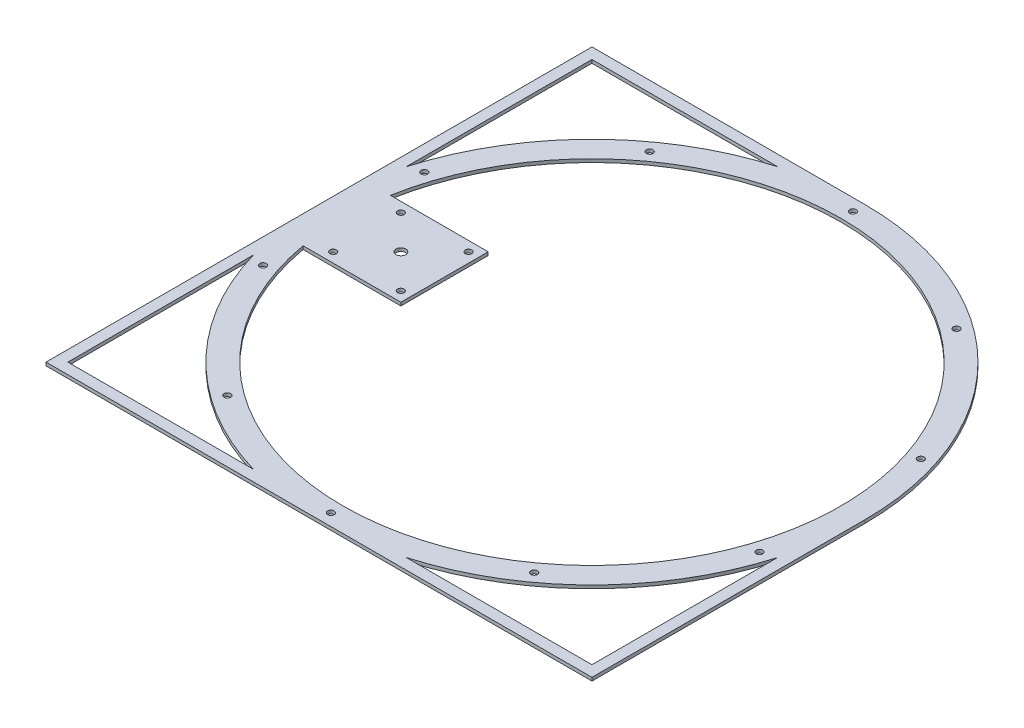
SolidWorks part; units mm, degrees
ref_plane "Front Plane" through (0, 0, 0) normal (0, 0, 1) x (1, 0, 0)
ref_plane "Top Plane" through (0, 0, 0) normal (0, 1, 0) x (1, 0, 0)
ref_plane "Right Plane" through (0, 0, 0) normal (1, 0, 0) x (0, 0, -1)
sketch "Sketch1" plane through (0, 0, 0) normal (0, 1, 0) x (1, 0, 0)
  line L0 (-125, 0) -> (-125, -5.475) construction
  line L1 (0, 0) -> (-250, 0)
  line L2 (0, 0) -> (0, -250)
  line L3 (0, -250) -> (-250, -250)
  line L4 (-250, 0) -> (-250, -250)
  circle A0 centre (-125, -125) radius 125
  circle A1 centre (-125, -5.475) radius 1.5
  circle A2 centre (-11.325, -88.0647) radius 1.5
  circle A3 centre (-54.745, -221.6978) radius 1.5
  circle A4 centre (-195.255, -221.6978) radius 1.5
  circle A5 centre (-238.675, -88.0647) radius 1.5
  circle A6 centre (-54.745, -28.3022) radius 1.5
  circle A7 centre (-11.325, -88.0647) radius 1.5
  circle A8 centre (-11.325, -161.9353) radius 1.5
  circle A9 centre (-54.745, -221.6978) radius 1.5
  circle A10 centre (-125, -244.525) radius 1.5
  circle A11 centre (-195.255, -221.6978) radius 1.5
  circle A12 centre (-238.675, -161.9353) radius 1.5
  circle A13 centre (-238.675, -88.0647) radius 1.5
  circle A14 centre (-195.255, -28.3022) radius 1.5
  point P21 (-125, -125)
  point P40 (-125, -125)
  dimension "D2" = 3
  dimension "D1" = 250
  dimension "D3" = 5
  dimension "D4" = 10
extrude "Boss-Extrude1" add sketch "Sketch1" along normal blind 1.5
sketch "Sketch2" plane through (0, 1.5, 0) normal (0, 1, 0) x (1, 0, 0)
  line L0 (-250, 0) -> (0, -250) construction
  line L1 (-228, -109.5) -> (-197, -109.5) construction
  line L2 (-228, -109.5) -> (-228, -140.5) construction
  line L3 (-228, -140.5) -> (-197, -140.5) construction
  line L4 (-197, -109.5) -> (-197, -140.5) construction
  line L5 (0, 0) -> (-250, -250) construction
  line L6 (-228, -109.5) -> (-197, -140.5) construction
  line L7 (-197, -109.5) -> (-228, -140.5) construction
  line L8 (-212.5, -125) -> (-125, -125) construction
  line L9 (-134.2026, -94.7801) -> (-214.277, -119.1646)
  line L10 (-214.277, -130.8354) -> (-134.2026, -155.2199)
  circle A0 centre (-228, -109.5) radius 1.5
  circle A1 centre (-197, -109.5) radius 1.5
  circle A2 centre (-197, -140.5) radius 1.5
  circle A3 centre (-228, -140.5) radius 1.5
  circle A4 centre (-125, -125) radius 31.59 construction
  circle A5 centre (-212.5, -125) radius 6.1 construction
  circle A6 centre (-212.5, -125) radius 2.25
  arc A7 (-214.277, -119.1646) -> (-214.277, -130.8354) centre (-212.5, -125) ccw
  arc A8 (-134.2026, -94.7801) -> (-134.2026, -155.2199) centre (-125, -125) cw
  dimension "D2" = 3
  dimension "D3" = 3
  dimension "D4" = 3
  dimension "D5" = 3
  dimension "D6" = 63.18
  dimension "D7" = 12.2
  dimension "D8" = 4.5
  dimension "D9" = 87.5
  dimension "D1" = 31
extrude "Cut-Extrude1" cut sketch "Sketch2" against normal blind 2 contours A6 | A3 | A0 | A1 | A2
sketch "Sketch3" plane through (0, 1.5, 0) normal (0, 1, 0) x (1, 0, 0)
  line L0 (0, 0) -> (-250, -250) construction
  line L1 (-250, 0) -> (0, -250) construction
  line L2 (-125, 0) -> (-125, -10.95)
  line L3 (-250, 0) -> (0, 0)
  line L4 (-250, 0) -> (-250, -250)
  line L5 (-250, -250) -> (0, -250)
  line L6 (0, 0) -> (0, -250)
  line L7 (-245, -5) -> (-160, -5)
  line L8 (-250, 0) -> (-245, 0)
  line L9 (-250, 0) -> (-250, -5)
  line L10 (-250, -5) -> (-245, -5)
  line L11 (-245, 0) -> (-245, -5)
  line L12 (-245, -5) -> (-245, -90)
  line L13 (-5, -5) -> (-90, -5)
  line L14 (-5, -5) -> (-5, -90)
  line L15 (-5, -245) -> (-5, -160)
  line L16 (-5, -245) -> (-90, -245)
  line L17 (-245, -245) -> (-160, -245)
  line L18 (-245, -245) -> (-245, -160)
  line L19 (-232.5, -105) -> (-237.2827, -105)
  line L20 (-232.5, -145) -> (-192.5, -145)
  line L21 (-232.5, -145) -> (-232.5, -105)
  line L22 (-232.5, -105) -> (-192.5, -105)
  line L23 (-192.5, -145) -> (-192.5, -105)
  line L24 (-232.5, -145) -> (-192.5, -105) construction
  line L25 (-232.5, -105) -> (-192.5, -145) construction
  line L26 (-232.5, -145) -> (-237.2827, -145)
  circle A1 centre (-125, -125) radius 125
  circle A2 centre (-125, -125) radius 114.05
  arc A3 (-245, -90) -> (-160, -5) centre (-125, -125) cw
  arc A4 (-90, -5) -> (-5, -90) centre (-125, -125) cw
  arc A5 (-5, -160) -> (-90, -245) centre (-125, -125) cw
  arc A6 (-160, -245) -> (-245, -160) centre (-125, -125) cw
  arc A7 (-237.2827, -105) -> (-237.2827, -145) centre (-125, -125) ccw
  point P22 (-212.5, -125)
  point P34 (-125, -125)
  dimension "D1" = 4
extrude "Cut-Extrude2" cut sketch "Sketch3" against normal blind 2 contours A1 L7 L12 | A1 L18 L17 | A1 L16 L15 | A1 L14 L13 | A2 L19 L22 L23 L20 L26
sketch "Sketch4" plane through (0, 1.5, 0) normal (0, 1, 0) x (1, 0, 0)
  line L0 (0, 0) -> (-250, 0) construction
  line L5 (0, 0) -> (0, -250) construction
  line L6 (-125, 0) -> (0, 0)
  line L7 (0, 0) -> (0, -125)
  arc A0 (-125, 0) -> (0, -125) centre (-125, -125) cw
extrude "Cut-Extrude3" cut sketch "Sketch4" against normal blind 2
